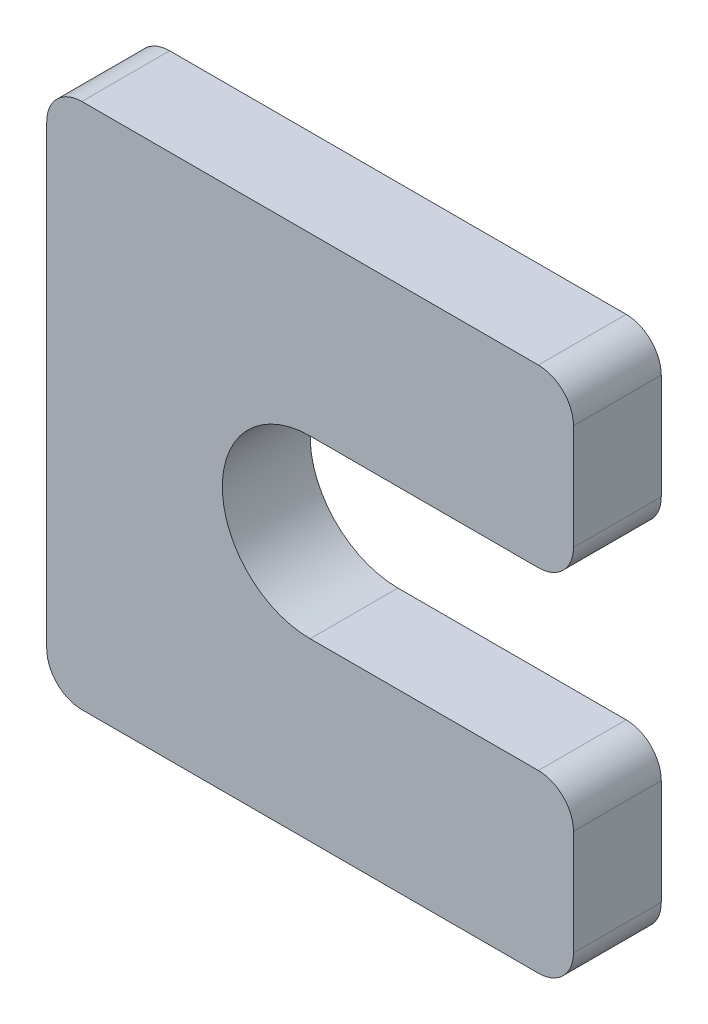
SolidWorks part; units mm, degrees
ref_plane "Plan de face" through (0, 0, 0) normal (0, 0, 1) x (1, 0, 0)
ref_plane "Plan de dessus" through (0, 0, 0) normal (0, 1, 0) x (1, 0, 0)
ref_plane "Plan de droite" through (0, 0, 0) normal (1, 0, 0) x (0, 0, -1)
sketch "Esquisse1" plane through (0, 0, 0) normal (0, 0, 1) x (1, 0, 0)
  line L1 (0, 0) -> (30, 0)
  line L2 (0, 0) -> (0, 30)
  line L3 (0, 30) -> (30, 30)
  line L4 (30, 0) -> (30, 30)
  dimension "D1" = 30
  dimension "D2" = 30
extrude "Boss.-Extru.1" add sketch "Esquisse1" along normal blind 5
sketch "Esquisse2" plane through (0, 0, 5) normal (0, 0, 1) x (1, 0, 0)
  line L0 (0, 0) -> (30, 30) construction
  circle A0 centre (15, 15) radius 5
  dimension "D1" = 10
extrude "Enlèv. mat.-Extru.1" cut sketch "Esquisse2" against normal through all both and the other way through all
sketch "Esquisse3" plane through (0, 0, 5) normal (0, 0, 1) x (1, 0, 0)
  line L0 (15, 10) -> (30, 10)
  line L1 (30, 0) -> (30, 30) construction
  line L2 (30, 10) -> (30, 20)
  line L3 (30, 20) -> (15, 20)
  line L4 (15, 20) -> (15, 10)
  line L5 (15, 10) -> (15, 0) construction
  line L6 (0, 0) -> (30, 0) construction
  circle A0 centre (15, 15) radius 5 construction
extrude "Enlèv. mat.-Extru.2" cut sketch "Esquisse3" against normal through all both and the other way through all
fillet "Congé1" radius 2 6 edges at (30, 10, 2.5) (30, 20, 2.5) (30, 30, 2.5) (30, 0, 2.5) (0, 0, 2.5) (0, 30, 2.5)
